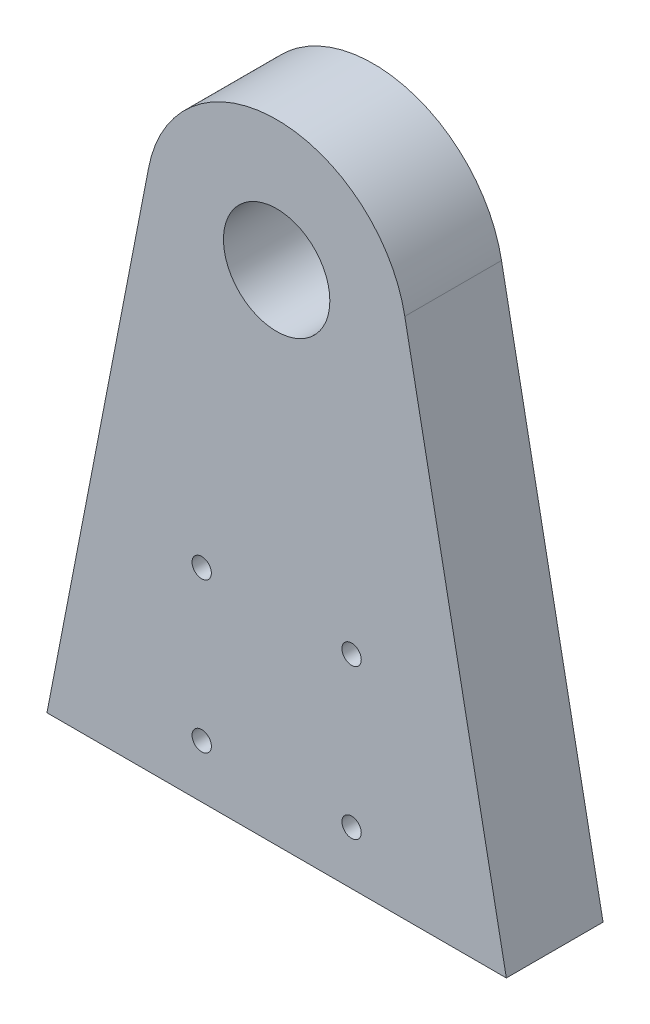
SolidWorks part; units mm, degrees
ref_plane "Front" through (0, 0, 0) normal (0, 0, 1) x (1, 0, 0)
ref_plane "Top" through (0, 0, 0) normal (0, 1, 0) x (1, 0, 0)
ref_plane "Right" through (0, 0, 0) normal (1, 0, 0) x (0, 0, -1)
sketch "Esquisse1" plane through (0, 0, 0) normal (0, 0, 1) x (1, 0, 0)
  line L0 (0, 0) -> (95, 0)
  line L1 (95, 0) -> (74, 108)
  line L2 (21, 108) -> (0, 0)
  arc A0 (74, 108) -> (21, 108) centre (47.5, 103.0398) ccw
  circle A1 centre (47.5, 103.0398) radius 11
  point P6 (47.5, 130)
  dimension "D4" = 22
  dimension "D1" = 95
  dimension "D2" = 130
  dimension "D3" = 108
  dimension "D5" = 21
  dimension "D6" = 21
extrude "Boss.-Extru.1" add sketch "Esquisse1" along normal blind 20
sketch "Esquisse2" plane through (0, 0, 20) normal (0, 0, 1) x (1, 0, 0)
  line L0 (0, 0) -> (95, 0) construction
  circle A0 centre (63, 11) radius 2
  circle A1 centre (32, 11) radius 2
  circle A2 centre (32, 42) radius 2
  circle A3 centre (63, 42) radius 2
  point P5 (0, 0)
  point P6 (0, 0)
  dimension "D1" = 11
  dimension "D2" = 32
  dimension "D3" = 4
  dimension "D6" = 31
  dimension "D7" = 31
  dimension "D4" = 2
  dimension "D5" = 2
extrude "Enlèv. mat.-Extru.1" cut sketch "Esquisse2" against normal through all
